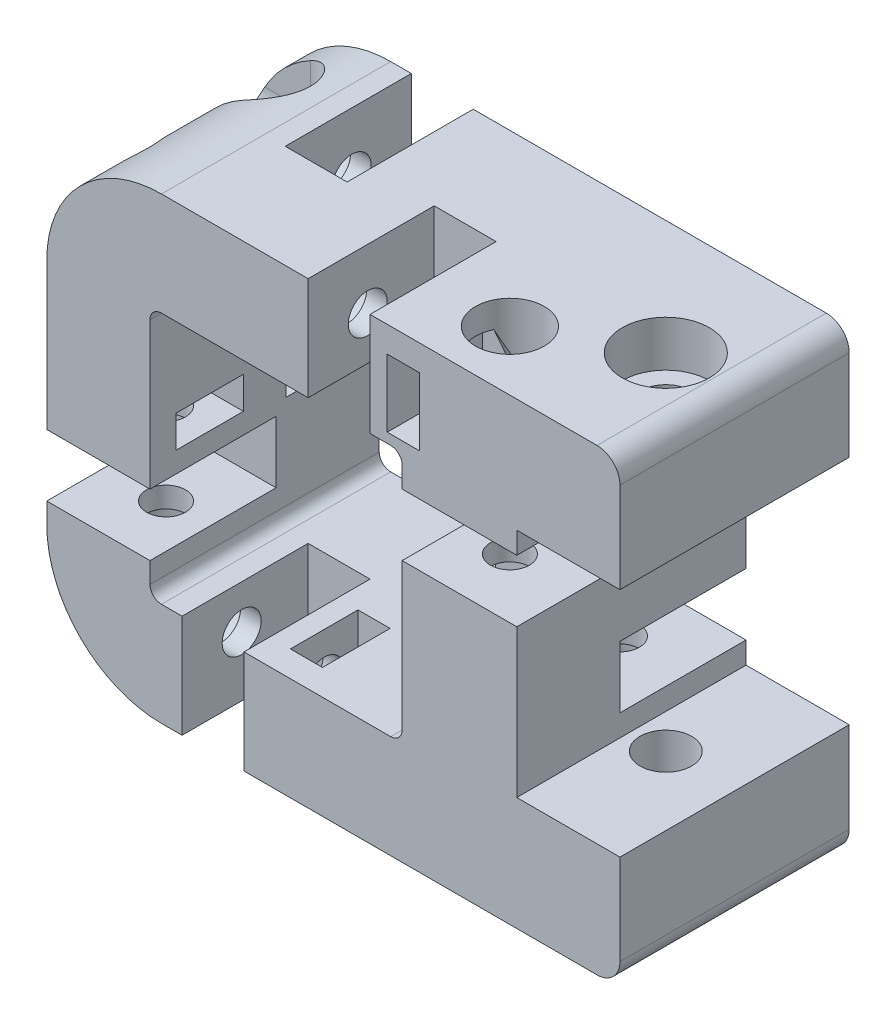
SolidWorks part; units mm, degrees
ref_plane "Alzado" through (0, 0, 0) normal (0, 0, 1) x (1, 0, 0)
ref_plane "Planta" through (0, 0, 0) normal (0, 1, 0) x (1, 0, 0)
ref_plane "Vista lateral" through (0, 0, 0) normal (1, 0, 0) x (0, 0, -1)
sketch "Croquis1" plane through (0, 0, 0) normal (0, 0, 1) x (1, 0, 0)
  line L0 (-10, 20) -> (10, 20)
  line L1 (-10, 11) -> (10, 11)
  line L2 (-11, 10) -> (-11, -10)
  line L3 (-10, -11) -> (10, -11)
  line L4 (11, 10) -> (11, -10)
  line L5 (-11, 11) -> (11, -11) construction
  line L6 (-11, -11) -> (11, 11) construction
  line L7 (20, 10) -> (20, -10)
  line L8 (-10, -20) -> (10, -20)
  line L9 (-20, 10) -> (-20, -10)
  line L10 (0, 0) -> (48.5028, 0) construction
  line L11 (10, -20) -> (28, -20)
  line L15 (30, 18) -> (30, -18)
  line L19 (10, 20) -> (28, 20)
  arc A0 (-11, -10) -> (-10, -11) centre (-10, -10) ccw
  arc A1 (10, -11) -> (11, -10) centre (10, -10) ccw
  arc A2 (11, 10) -> (10, 11) centre (10, 10) ccw
  arc A3 (-10, 11) -> (-11, 10) centre (-10, 10) ccw
  arc A4 (20, 10) -> (10, 20) centre (10, 10) ccw
  arc A5 (10, -20) -> (20, -10) centre (10, -10) ccw
  arc A6 (-20, -10) -> (-10, -20) centre (-10, -10) ccw
  arc A7 (-10, 20) -> (-20, 10) centre (-10, 10) ccw
  arc A8 (28, -20) -> (30, -18) centre (28, -18) ccw
  arc A9 (30, 18) -> (28, 20) centre (28, 18) ccw
  point P0 (0, 0)
  point P32 (25, 0)
  dimension "D3" = 1
  dimension "D4" = 10
  dimension "D6" = 2
  dimension "D1" = 22
  dimension "D2" = 22
  dimension "D5" = 9
extrude "Saliente-Extruir1" add sketch "Croquis1" along normal blind 20 contours L0 A7 L9 A6 L8 A5 L7 A4 A3 L1 A2 L4 A1 L3 A0 L2 | L15 A9 L19 A4 L7 A5 L11 A8
sketch "Croquis2" plane through (0, 0, 20) normal (0, 0, 1) x (1, 0, 0)
  line L0 (-10, -11) -> (10, -11) construction
  line L1 (-8.2, -1) -> (-2.8, -1)
  line L2 (-8.2, -1) -> (-8.2, -21)
  line L3 (-8.2, -21) -> (-2.8, -21)
  line L4 (-2.8, -1) -> (-2.8, -21)
  line L5 (-8.2, -1) -> (-2.8, -21) construction
  line L6 (-8.2, -21) -> (-2.8, -1) construction
  line L7 (-11, 10) -> (-11, -10) construction
  line L8 (-1, -8.2) -> (-21, -8.2)
  line L9 (-1, -8.2) -> (-1, -2.8)
  line L10 (-1, -2.8) -> (-21, -2.8)
  line L11 (-21, -8.2) -> (-21, -2.8)
  line L12 (-1, -8.2) -> (-21, -2.8) construction
  line L13 (-1, -2.8) -> (-21, -8.2) construction
  line L14 (11, 10) -> (11, -10) construction
  line L15 (1, 8.2) -> (21, 8.2)
  line L16 (1, 8.2) -> (1, 2.8)
  line L17 (1, 2.8) -> (21, 2.8)
  line L18 (21, 8.2) -> (21, 2.8)
  line L19 (1, 8.2) -> (21, 2.8) construction
  line L20 (1, 2.8) -> (21, 8.2) construction
  line L21 (-10, 11) -> (10, 11) construction
  line L22 (8.2, 1) -> (2.8, 1)
  line L23 (8.2, 1) -> (8.2, 21)
  line L24 (8.2, 21) -> (2.8, 21)
  line L25 (2.8, 1) -> (2.8, 21)
  line L26 (8.2, 1) -> (2.8, 21) construction
  line L27 (8.2, 21) -> (2.8, 1) construction
  point P0 (-5.5, -11)
  point P7 (-11, -5.5)
  point P14 (11, 5.5)
  point P22 (5.5, 11)
  line M1 (-10, -20) -> (28, -20)
  line M5 (28, 20) -> (-10, 20)
  line M7 (-20, 10) -> (-20, -10)
  line M10 (-10, 11) -> (10, 11)
  line M12 (11, 10) -> (11, -10)
  line M14 (10, -11) -> (-10, -11)
  line M16 (-11, -10) -> (-11, 10)
  dimension "D1" = 5.5
  dimension "D2" = 5.5
  dimension "D3" = 20
  dimension "D4" = 20
  dimension "D5" = 5.4
  dimension "D6" = 5.4
  dimension "D7" = 5.5
  dimension "D8" = 5.4
  dimension "D9" = 20
  dimension "D10" = 5.5
  dimension "D11" = 5.4
  dimension "D12" = 20
extrude "Cortar-Extruir1" cut sketch "Croquis2" against normal blind 11 contours L10 L8 M16 M7 | L4 L2 M14 M1 | L18 L15 L17 M12 | L25 L23 M10 M5
sketch "Croquis3" plane through (0, 0, 0) normal (0, 0, -1) x (-1, 0, 0)
  line L0 (-8.2, -1) -> (-2.8, -1)
  line L1 (-8.2, -1) -> (-8.2, -21)
  line L2 (-8.2, -21) -> (-2.8, -21)
  line L3 (-2.8, -1) -> (-2.8, -21)
  line L4 (-8.2, -1) -> (-2.8, -21) construction
  line L5 (-8.2, -21) -> (-2.8, -1) construction
  line L6 (-1, -8.2) -> (-21, -8.2)
  line L7 (-1, -8.2) -> (-1, -2.8)
  line L8 (-1, -2.8) -> (-21, -2.8)
  line L9 (-21, -8.2) -> (-21, -2.8)
  line L10 (-1, -8.2) -> (-21, -2.8) construction
  line L11 (-1, -2.8) -> (-21, -8.2) construction
  line L12 (1, 8.2) -> (21, 8.2)
  line L13 (1, 8.2) -> (1, 2.8)
  line L14 (1, 2.8) -> (21, 2.8)
  line L15 (21, 8.2) -> (21, 2.8)
  line L16 (1, 8.2) -> (21, 2.8) construction
  line L17 (1, 2.8) -> (21, 8.2) construction
  line L18 (8.2, 1) -> (2.8, 1)
  line L19 (8.2, 1) -> (8.2, 21)
  line L20 (8.2, 21) -> (2.8, 21)
  line L21 (2.8, 1) -> (2.8, 21)
  line L22 (8.2, 1) -> (2.8, 21) construction
  line L23 (8.2, 21) -> (2.8, 1) construction
  line L24 (-2.8, -1) -> (2.8, 1) construction
  line L25 (1, 2.8) -> (-1, -2.8) construction
  point P0 (-5.5, -11)
  point P5 (-11, -5.5)
  point P10 (11, 5.5)
  point P15 (5.5, 11)
  point P20 (0, 0)
  line M1 (-28, -20) -> (10, -20)
  line M3 (20, -10) -> (20, 10)
  line M5 (10, 20) -> (-28, 20)
  line M10 (11, 10) -> (11, -10)
  line M12 (10, -11) -> (-10, -11)
  line M14 (-11, -10) -> (-11, 10)
  line M16 (-10, 11) -> (10, 11)
  dimension "D1" = 20
  dimension "D2" = 20
  dimension "D3" = 5.4
  dimension "D4" = 5.4
  dimension "D5" = 5.4
  dimension "D6" = 20
  dimension "D7" = 5.4
  dimension "D8" = 20
extrude "Cortar-Extruir2" cut sketch "Croquis3" against normal blind 11 contours L21 L19 M16 M5 | L14 L12 M10 M3 | L3 L1 M12 M1 | L9 L6 L8 M14
sketch "Croquis4" plane through (30, 0, 0) normal (1, 0, 0) x (0, 0, -1)
  line L0 (-20, 0) -> (0, 0) construction
  line L1 (-20, 18) -> (-20, -18) construction
  line L2 (0, 18) -> (0, -18) construction
  line L4 (-20, 10.1) -> (0, 10.1)
  line L5 (-20, 10.1) -> (-20, -10.1)
  line L6 (-20, -10.1) -> (0, -10.1)
  line L7 (0, 10.1) -> (0, -10.1)
  line L8 (-20, 10.1) -> (0, -10.1) construction
  line L9 (-20, -10.1) -> (0, 10.1) construction
  point P6 (-10, 0)
  dimension "D1" = 20.2
extrude "Cortar-Extruir3" cut sketch "Croquis4" against normal up to surface (9 mm away) up to face at (21, 5.5, 14.5)
sketch "Croquis5" plane through (0, -10.1, 0) normal (0, 1, 0) x (1, 0, 0)
  line L0 (21, -10) -> (30, -10) construction
  line L1 (21, -20) -> (21, 0) construction
  line L2 (30, -20) -> (30, 0) construction
  circle A0 centre (24, -10) radius 2.25
  dimension "D2" = 4.5
  dimension "D1" = 3
extrude "Cortar-Extruir4" cut sketch "Croquis5" against normal mid plane 64
sketch "Croquis6" plane through (0, 20, 0) normal (0, 1, 0) x (1, 0, 0)
  circle A0 centre (24, -10) radius 3.8
extrude "Cortar-Extruir5" cut sketch "Croquis6" against normal blind 4
sketch "Croquis7" plane through (0, -20, 0) normal (0, -1, 0) x (1, 0, 0)
  circle A0 centre (24, 10) radius 3.8
extrude "Cortar-Extruir6" cut sketch "Croquis7" against normal blind 4
ref_plane "Plano3" through (-20, 0, 0) normal (-1, 0, 0) x (0, 0, 1)
sketch "Croquis8" plane through (-20, 0, 0) normal (-1, 0, 0) x (0, 0, 1)
  line L0 (0, 20) -> (0, 10) construction
  line L1 (20, 10) -> (20, 20) construction
  line L2 (20, 20) -> (0, 20) construction
  line L3 (20, -20) -> (0, -20) construction
  line L4 (0, -10) -> (0, -20) construction
  line L5 (20, -20) -> (20, -10) construction
  circle A0 centre (5.2, 14.8) radius 1.7
  circle A1 centre (14.8, 14.8) radius 1.7
  circle A2 centre (5.2, -14.8) radius 1.7
  circle A3 centre (14.8, -14.8) radius 1.7
  point P16 (0, -15)
  dimension "D1" = 3.4
  dimension "D2" = 3.4
  dimension "D8" = 3.4
  dimension "D10" = 3.4
  dimension "D3" = 5.2
  dimension "D4" = 5.2
  dimension "D5" = 5.2
  dimension "D6" = 5.2
  dimension "D7" = 5.2
  dimension "D9" = 5.2
  dimension "D11" = 5.2
  dimension "D12" = 5.2
extrude "Cortar-Extruir7" cut sketch "Croquis8" against normal blind 23
sketch "Croquis9" plane through (-20, 0, 0) normal (-1, 0, 0) x (0, 0, 1)
  circle A0 centre (14.8, 14.8) radius 1.7
  circle A1 centre (5.2, -14.8) radius 1.7
  dimension "D1" = 3.4
  dimension "D2" = 3.4
extrude "Cortar-Extruir8" cut sketch "Croquis9" against normal blind 34
sketch "Croquis10" plane through (-20, 0, 0) normal (-1, 0, 0) x (0, 0, 1)
  circle A0 centre (5.2, 14.8) radius 3
  circle A1 centre (14.8, 14.8) radius 3
  circle A2 centre (14.8, -14.8) radius 3
  circle A3 centre (5.2, -14.8) radius 3
  dimension "D1" = 6
  dimension "D2" = 6
  dimension "D3" = 6
  dimension "D4" = 6
extrude "Cortar-Extruir9" cut sketch "Croquis10" against normal blind 10
sketch "Croquis11" plane through (-20, 0, 0) normal (-1, 0, 0) x (0, 0, 1)
  circle A0 centre (14.8, 14.8) radius 3
  circle A1 centre (5.2, -14.8) radius 3
  dimension "D1" = 6
  dimension "D2" = 6
extrude "Cortar-Extruir10" cut sketch "Croquis11" against normal blind 21
ref_plane "Plano4" through (0, 20, 0) normal (0, 1, 0) x (1, 0, 0)
sketch "Croquis12" plane through (0, 20, 0) normal (0, 1, 0) x (1, 0, 0)
  line L0 (-20, 13.1465) -> (-20, -13.1465) construction
  line L2 (-10, 0) -> (-20, 0) construction
  circle A0 centre (-14.8, -5.2) radius 1.7
  dimension "D1" = 3.4
  dimension "D3" = 5.2
  dimension "D6" = 5.2
extrude "Cortar-Extruir11" cut sketch "Croquis12" against normal blind 23
sketch "Croquis13" plane through (0, 20, 0) normal (0, 1, 0) x (1, 0, 0)
  circle A0 centre (-14.8, -5.2) radius 3
  dimension "D1" = 6
extrude "Cortar-Extruir12" cut sketch "Croquis13" against normal blind 10
sketch "Croquis14" plane through (0, 20, 0) normal (0, 1, 0) x (1, 0, 0)
  line L1 (-14.8, -2.2) -> (-20.8, -2.2)
  line L2 (-14.8, -2.2) -> (-14.8, -8.2)
  line L3 (-14.8, -8.2) -> (-20.8, -8.2)
  line L4 (-20.8, -2.2) -> (-20.8, -8.2)
  dimension "D1" = 6
  dimension "D2" = 6
extrude "Cortar-Extruir13" cut sketch "Croquis14" against normal blind 5.2
sketch "Croquis15" plane through (0, -20, 0) normal (0, -1, 0) x (1, 0, 0)
  line L0 (-10, 20) -> (-8.2, 20) construction
  line L1 (-20, 20) -> (-20, 0) construction
  circle A0 centre (-14.8, 14.8) radius 1.7
  dimension "D3" = 3.4
  dimension "D1" = 5.2
  dimension "D2" = 5.2
extrude "Cortar-Extruir14" cut sketch "Croquis15" against normal blind 23
sketch "Croquis16" plane through (0, -20, 0) normal (0, -1, 0) x (-1, 0, 0)
  circle A0 centre (14.8, -14.8) radius 3
extrude "Cortar-Extruir15" cut sketch "Croquis16" against normal blind 10
sketch "Croquis17" plane through (0, -20, 0) normal (0, -1, 0) x (1, 0, 0)
  line L1 (-14.8, 17.8) -> (-20.8, 17.8)
  line L2 (-14.8, 17.8) -> (-14.8, 11.8)
  line L3 (-14.8, 11.8) -> (-20.8, 11.8)
  line L4 (-20.8, 17.8) -> (-20.8, 11.8)
  dimension "D1" = 6
  dimension "D2" = 6
extrude "Cortar-Extruir16" cut sketch "Croquis17" against normal blind 5.2
sketch "Croquis18" plane through (0, -20, 0) normal (0, -1, 0) x (1, 0, 0)
  line L0 (8.2, 0) -> (28, 0) construction
  line L1 (11, 11) -> (11, 0) construction
  circle A0 centre (15.2, 5.2) radius 1.7
  dimension "D1" = 3.4
  dimension "D2" = 5.2
  dimension "D3" = 4.2
extrude "Cortar-Extruir17" cut sketch "Croquis18" against normal blind 23
sketch "Croquis19" plane through (0, -20, 0) normal (0, -1, 0) x (-1, 0, 0)
  circle A0 centre (-15.2, -5.2) radius 3
extrude "Cortar-Extruir18" cut sketch "Croquis19" against normal blind 10
sketch "Croquis20" plane through (0, 20, 0) normal (0, 1, 0) x (1, 0, 0)
  line L0 (8.2, -20) -> (28, -20) construction
  line L1 (11, -9) -> (11, -20) construction
  circle A0 centre (15.2, -14.8) radius 1.7
  dimension "D1" = 5.2
  dimension "D2" = 4.2
extrude "Cortar-Extruir19" cut sketch "Croquis20" against normal blind 23
sketch "Croquis21" plane through (0, 20, 0) normal (0, 1, 0) x (1, 0, 0)
  circle A0 centre (15.2, -14.8) radius 3
extrude "Cortar-Extruir20" cut sketch "Croquis21" against normal blind 10
sketch "Croquis22" plane through (0, -11, 0) normal (0, 1, 0) x (1, 0, 0)
  line L0 (-2.8, -20) -> (10, -20) construction
  line L1 (1.8, -11.85) -> (-1, -11.85)
  line L2 (1.8, -11.85) -> (1.8, -17.75)
  line L3 (1.8, -17.75) -> (-1, -17.75)
  line L4 (-1, -11.85) -> (-1, -17.75)
  line L5 (1.8, -11.85) -> (-1, -17.75) construction
  line L6 (1.8, -17.75) -> (-1, -11.85) construction
  line L13 (-2.8, -9) -> (-2.8, -20) construction
  line L14 (2.8, -11) -> (2.8, 0) construction
  line L17 (-2.8, -9) -> (-8.2, -9) construction
  line L18 (-2.8, -9) -> (-1, -11.85) construction
  line L20 (2.8, -11) -> (8.2, -11) construction
  line L21 (2.8, -11) -> (1.8, -11.85) construction
  point P0 (0.4, -14.8)
  dimension "D1" = 5.2
  dimension "D2" = 1.8
  dimension "D5" = 2.8
  dimension "D7" = 5.9
extrude "Cortar-Extruir21" cut sketch "Croquis22" against normal blind 7.3
sketch "Croquis23" plane through (-11, 0, 0) normal (1, 0, 0) x (0, 0, -1)
  line L7 (-17.75, -1) -> (-11.85, -1)
  line L16 (-9, -2.8) -> (-8.15, -1.8) construction
  line L17 (-11.85, -1) -> (-9, -2.8) construction
  line L18 (-11, 2.8) -> (-8.15, 1) construction
  line L19 (-11.85, 1.8) -> (-11, 2.8) construction
  line L20 (-11.85, -1) -> (-17.75, 1.8) construction
  line L21 (-17.75, -1) -> (-11.85, 1.8) construction
  line L22 (-2.25, -1.8) -> (-8.15, 1) construction
  line L23 (-8.15, -1.8) -> (-2.25, 1) construction
  line L24 (-17.75, 1.8) -> (-11.85, 1.8)
  line L25 (-11.85, -1) -> (-11.85, 1.8)
  line L26 (-17.75, -1) -> (-17.75, 1.8)
  line L27 (-8.15, 1) -> (-2.25, 1)
  line L28 (-2.25, -1.8) -> (-2.25, 1)
  line L29 (-8.15, -1.8) -> (-2.25, -1.8)
  line L30 (-8.15, -1.8) -> (-8.15, 1)
  point P42 (-14.8, 0.4)
  point P43 (-5.2, -0.4)
  dimension "D4" = 5.9
extrude "Cortar-Extruir22" cut sketch "Croquis23" against normal blind 7.3
sketch "Croquis24" plane through (11, 0, 0) normal (-1, 0, 0) x (0, 0, 1)
  line L0 (11, -8.2) -> (11, -2.8) construction
  line L1 (11, -2.8) -> (0, -2.8) construction
  line L7 (2.25, -1) -> (8.15, -1)
  line L16 (11, -2.8) -> (11.85, -1.8) construction
  line L17 (8.15, -1) -> (11, -2.8) construction
  line L18 (9, 2.8) -> (11.85, 1) construction
  line L19 (8.15, 1.8) -> (9, 2.8) construction
  line L20 (8.15, -1) -> (2.25, 1.8) construction
  line L21 (2.25, -1) -> (8.15, 1.8) construction
  line L22 (17.75, -1.8) -> (11.85, 1) construction
  line L23 (11.85, -1.8) -> (17.75, 1) construction
  line L24 (2.25, 1.8) -> (8.15, 1.8)
  line L25 (8.15, -1) -> (8.15, 1.8)
  line L26 (2.25, -1) -> (2.25, 1.8)
  line L27 (11.85, 1) -> (17.75, 1)
  line L28 (17.75, -1.8) -> (17.75, 1)
  line L29 (11.85, -1.8) -> (17.75, -1.8)
  line L30 (11.85, -1.8) -> (11.85, 1)
  point P0 (11, -2.8)
  point P42 (5.2, 0.4)
  point P43 (14.8, -0.4)
  dimension "D4" = 5.9
extrude "Cortar-Extruir23" cut sketch "Croquis24" against normal blind 7.3
sketch "Croquis25" plane through (0, 11, 0) normal (0, -1, 0) x (1, 0, 0)
  line L0 (1.8, 8.15) -> (-1, 8.15)
  line L1 (1.8, 8.15) -> (1.8, 2.25)
  line L2 (1.8, 2.25) -> (-1, 2.25)
  line L3 (-1, 8.15) -> (-1, 2.25)
  line L4 (1.8, 8.15) -> (-1, 2.25) construction
  line L5 (1.8, 2.25) -> (-1, 8.15) construction
  line L13 (-2.8, 11) -> (-1, 8.15) construction
  line L15 (2.8, 9) -> (1.8, 8.15) construction
  line L16 (2.8, 9) -> (8.2, 9) construction
  line L17 (2.8, 9) -> (2.8, 20) construction
  point P0 (0.4, 5.2)
  point P12 (2.8, 9)
  dimension "D1" = 2.8
  dimension "D3" = 5.9
extrude "Cortar-Extruir24" cut sketch "Croquis25" against normal blind 7.3
sketch "Croquis26" plane through (0, 0, 20) normal (0, 0, 1) x (1, 0, 0)
  line L0 (12.5, 17.75) -> (9.7, 17.75)
  line L1 (12.5, 17.75) -> (12.5, 11.85)
  line L2 (12.5, 11.85) -> (9.7, 11.85)
  line L3 (9.7, 17.75) -> (9.7, 11.85)
  line L4 (12.5, 17.75) -> (9.7, 11.85) construction
  line L5 (12.5, 11.85) -> (9.7, 17.75) construction
  line L6 (8.2, 20) -> (28, 20) construction
  line L7 (8.2, 11) -> (8.2, 20) construction
  point P0 (11.1, 14.8)
  point P9 (8.2, 11)
  dimension "D1" = 2.8
  dimension "D2" = 5.2
  dimension "D3" = 5.9
  dimension "D4" = 1.5
extrude "Cortar-Extruir25" cut sketch "Croquis26" against normal blind 8.3
sketch "Croquis27" plane through (0, 0, 0) normal (0, 0, -1) x (-1, 0, 0)
  line L0 (-12.5, -17.75) -> (-9.7, -17.75)
  line L1 (-12.5, -17.75) -> (-12.5, -11.85)
  line L2 (-12.5, -11.85) -> (-9.7, -11.85)
  line L3 (-9.7, -17.75) -> (-9.7, -11.85)
  line L4 (-12.5, -17.75) -> (-9.7, -11.85) construction
  line L5 (-12.5, -11.85) -> (-9.7, -17.75) construction
  point P0 (-11.1, -14.8)
  point P5 (-8.2, -11)
  point P6 (-8.2, -11)
  dimension "D1" = 2.8
  dimension "D2" = 5.9
extrude "Cortar-Extruir26" cut sketch "Croquis27" against normal blind 8.3
sketch "Croquis28" plane through (12.5, 0, 0) normal (-1, 0, 0) x (0, 0, 1)
  line L0 (6.5077, -11.85) -> (7.8, -14.8)
  line L1 (3.8923, -11.85) -> (6.5077, -11.85) construction
  line L2 (8.3, -11.85) -> (6.5077, -11.85) construction
  line L4 (7.8, -14.8) -> (6.5077, -17.75)
  line L5 (6.5077, -17.75) -> (6.5077, -15.8863) construction
  line L6 (6.5077, -17.75) -> (3.8923, -17.75)
  line L7 (3.8923, -17.75) -> (0, -17.75) construction
  line L8 (3.8923, -15.8863) -> (3.8923, -17.75) construction
  line L9 (3.8923, -17.75) -> (2.6, -14.8)
  line L10 (2.6, -14.8) -> (3.8923, -11.85)
  line L11 (3.8923, -11.85) -> (0, -11.85) construction
  line L14 (7.8, -14.8) -> (2.6, -14.8) construction
  line L16 (3.8923, -11.85) -> (6.5077, -11.85)
  line L17 (13.4923, 17.75) -> (12.2, 14.8)
  line L18 (13.4923, 17.75) -> (13.4923, 15.8863) construction
  line L19 (11.7, 17.75) -> (13.4923, 17.75) construction
  line L21 (12.2, 14.8) -> (13.4923, 11.85)
  line L24 (13.4923, 11.85) -> (16.1077, 11.85)
  line L25 (16.1077, 11.85) -> (20, 11.85) construction
  line L26 (16.1077, 11.85) -> (16.1077, 13.7137) construction
  line L27 (16.1077, 11.85) -> (17.4, 14.8)
  line L28 (17.4, 14.8) -> (16.1077, 17.75)
  line L29 (16.1077, 15.8863) -> (16.1077, 17.75) construction
  line L30 (16.1077, 17.75) -> (20, 17.75) construction
  line L31 (16.1077, 17.75) -> (13.4923, 17.75)
  line L32 (12.2, 14.8) -> (17.4, 14.8) construction
  line L33 (11.7, 11.85) -> (11.7, 17.75) construction
  line L34 (8.3, -11.85) -> (8.3, -17.75) construction
  dimension "D1" = 5.2
  dimension "D2" = 5.2
  dimension "D3" = 0.5
  dimension "D4" = 0.5
extrude "Cortar-Extruir27" cut sketch "Croquis28" against normal blind 3
sketch "Croquis29" plane through (0, 0, 2.2) normal (0, 0, 1) x (1, 0, 0)
  line L0 (-18.0353, 10) -> (-18.5353, 10)
  line L1 (-10, 18.0353) -> (-10, 18.5353)
  line L2 (-10, 19.2) -> (-10, 19.7)
  line L3 (-19.2, 10) -> (-19.7, 10)
  arc A0 (-10, 19.7) -> (-19.7, 10) centre (-10, 10) ccw
  arc A1 (-10, 18.0353) -> (-18.0353, 10) centre (-10, 10) ccw
  arc A2 (-10, 18.5353) -> (-18.5353, 10) centre (-10, 10) ccw
  arc A3 (-10, 19.2) -> (-19.2, 10) centre (-10, 10) ccw
  arc A5 (-14.8, 18.7727) -> (-18.7727, 14.8) centre (-10, 10) ccw construction
  dimension "D1" = 0.5
  dimension "D2" = 0.3
  dimension "D3" = 0.5
extrude "Soportes-1" [suppressed] add sketch "Croquis29" along normal blind 5.8
sketch "Croquis30" plane through (0, 0, 11.8) normal (0, 0, 1) x (1, 0, 0)
  line L0 (-18.0353, -10) -> (-18.5353, -10)
  line L1 (-10, -18.0353) -> (-10, -18.5353)
  line L2 (-19.2, -10) -> (-19.7, -10)
  line L3 (-10, -19.2) -> (-10, -19.7)
  arc A1 (-18.0353, -10) -> (-10, -18.0353) centre (-10, -10) ccw
  arc A2 (-18.5353, -10) -> (-10, -18.5353) centre (-10, -10) ccw
  arc A3 (-19.2, -10) -> (-10, -19.2) centre (-10, -10) ccw
  arc A4 (-19.7, -10) -> (-10, -19.7) centre (-10, -10) ccw
  point P4 (-10, -10)
  dimension "D1" = 8.0353
  dimension "D2" = 8.5353
  dimension "D3" = 9.2
  dimension "D4" = 0.5
extrude "Soportes-2" [suppressed] add sketch "Croquis30" along normal blind 5.8
